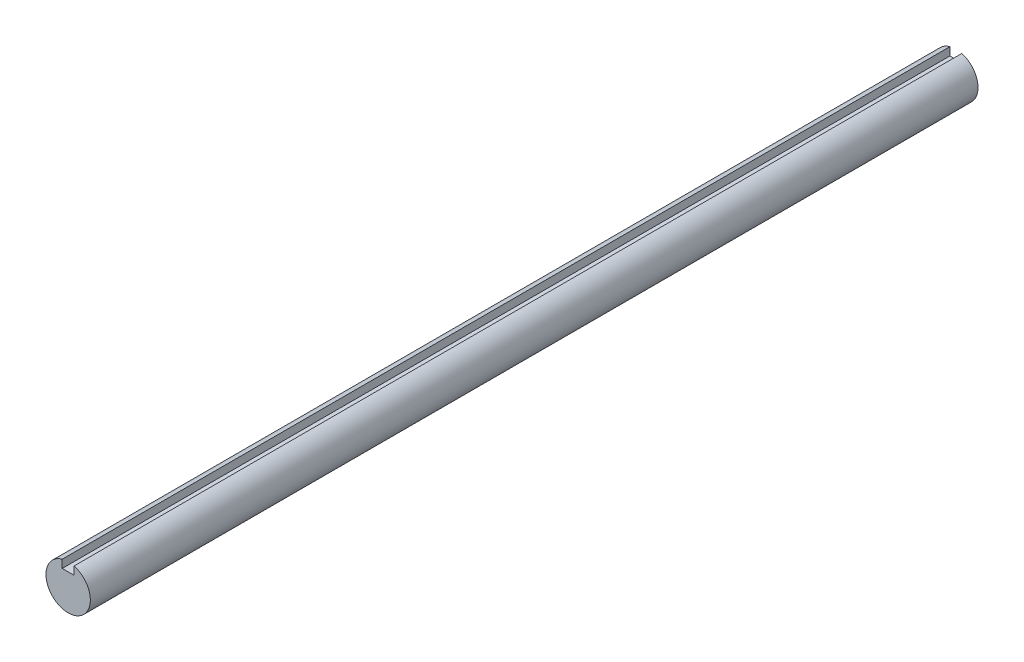
SolidWorks part; units mm, degrees
material "PETG"
ref_plane "Front Plane" through (0, 0, 0) normal (0, 0, 1) x (1, 0, 0)
ref_plane "Top Plane" through (0, 0, 0) normal (0, 1, 0) x (1, 0, 0)
ref_plane "Right Plane" through (0, 0, 0) normal (1, 0, 0) x (0, 0, -1)
sketch "Sketch1" plane through (0, 0, 0) normal (0, 0, 1) x (1, 0, 0)
  circle A0 centre (0, 0) radius 0.75
  dimension "D1" = 1.5
extrude "Boss-Extrude1" add sketch "Sketch1" along normal blind 30
sketch "Sketch3" plane through (0, 0, 30) normal (0, 0, 1) x (1, 0, 0)
  line L1 (0, 0.45) -> (0.2, 0.45)
  line L2 (0, 0.45) -> (0, 0.8075)
  line L3 (0, 0.8075) -> (0.2, 0.8075)
  line L4 (0.2, 0.45) -> (0.2, 0.8075)
  dimension "D1" = 0.45
  dimension "D2" = 0.2
  dimension "D3" = 0.2
extrude "Cut-Extrude1" cut sketch "Sketch3" against normal through all
mirror "Mirror1" about plane through (0, 0, 0) normal (1, 0, 0) of "Cut-Extrude1"
equation "\"rail width\"= 50"
equation "\"system width\"= 125"
equation "\"system depth\"= 250"
equation "\"internal height\"= 100"
equation "\"carriage height\"= 50"
equation "\"gear radius\"= 5"
equation "\"tooth width\"= 1"
equation "\"track width\"= 10"
equation "\"D1@Boss-Extrude1\"=\"track width\"*3"
